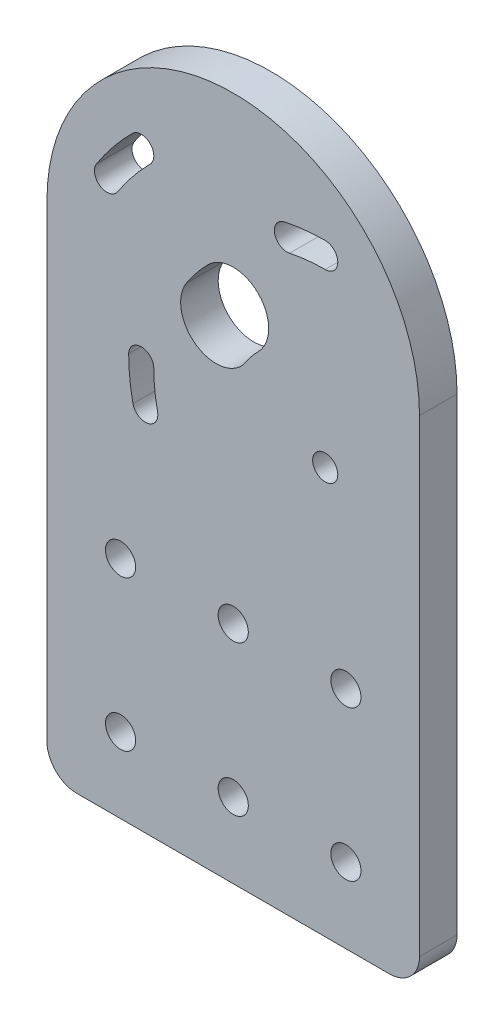
SolidWorks part; units mm, degrees
ref_plane "Front Plane" through (0, 0, 0) normal (0, 0, 1) x (1, 0, 0)
ref_plane "Top Plane" through (0, 0, 0) normal (0, 1, 0) x (1, 0, 0)
ref_plane "Right Plane" through (0, 0, 0) normal (1, 0, 0) x (0, 0, -1)
sketch "Sketch1" plane through (0, 0, 0) normal (0, 0, 1) x (1, 0, 0)
  line L0 (0, 0) -> (-11948.862, 0) construction
  line L1 (-0.5397, 50.8) -> (-11949.4017, 50.8) construction
  line L2 (31.5, 0) -> (31.5, 84.3)
  line L3 (-31.5, 84.3) -> (-31.5, 0)
  line L4 (-31.5, 0) -> (31.5, 0)
  line L5 (19.05, 12.7) -> (0, 12.7) construction
  line L6 (19.05, 12.7) -> (19.05, 38.1) construction
  line L7 (31.5, 12.7) -> (19.05, 12.7) construction
  line L8 (19.05, 12.7) -> (19.05, 0) construction
  line L9 (-31.5, 38.1) -> (-19.05, 38.1) construction
  line L10 (-19.05, 38.1) -> (-19.05, 50.8) construction
  line L11 (9.0877, 99.1765) -> (15.5563, 68.7437) construction
  line L12 (15.5563, 68.7437) -> (15.5563, 99.8563) construction
  line L13 (-15.5563, 68.7437) -> (15.5563, 68.7437) construction
  line L14 (15.5563, 68.7437) -> (-14.8765, 62.275) construction
  line L15 (-21.3452, 92.7078) -> (15.5563, 68.7437) construction
  line L16 (15.5563, 68.7437) -> (-15.5563, 99.8563) construction
  line L17 (-2.8944, 80.7257) -> (15.5563, 68.7437) construction
  line L18 (15.5563, 68.7437) -> (0, 84.3) construction
  circle A0 centre (0, 84.3) radius 33.5 construction
  circle A1 centre (0, 84.3) radius 22 construction
  circle A2 centre (-15.5563, 99.8563) radius 2.125 construction
  circle A3 centre (15.5563, 99.8563) radius 2.125 construction
  circle A4 centre (15.5563, 68.7437) radius 2.125
  circle A5 centre (-15.5563, 68.7437) radius 2.125 construction
  arc A6 (31.5, 84.3) -> (-31.5, 84.3) centre (0, 84.3) ccw
  circle A7 centre (19.05, 12.7) radius 2.5527
  circle A8 centre (0, 12.7) radius 2.5527
  circle A9 centre (0, 38.1) radius 2.5527
  circle A10 centre (19.05, 38.1) radius 2.5527
  circle A11 centre (-19.05, 12.7) radius 2.5527
  circle A12 centre (-19.05, 38.1) radius 2.5527
  circle A13 centre (0, 84.3) radius 6 construction
  arc A17 (9.0877, 99.1765) -> (15.5563, 99.8563) centre (15.5563, 68.7437) cw construction
  arc A18 (15.5563, 101.9813) -> (8.6458, 101.255) centre (15.5563, 68.7437) ccw
  arc A19 (15.5563, 97.7313) -> (9.5295, 97.0979) centre (15.5563, 68.7437) ccw
  arc A20 (15.5563, 97.7313) -> (15.5563, 101.9813) centre (15.5563, 99.8563) ccw
  arc A21 (8.6458, 101.255) -> (9.5295, 97.0979) centre (9.0877, 99.1765) ccw
  arc A22 (-15.5563, 68.7437) -> (-14.8765, 62.275) centre (15.5563, 68.7437) ccw construction
  arc A23 (-17.6813, 68.7437) -> (-16.955, 61.8331) centre (15.5563, 68.7437) ccw
  arc A24 (-13.4313, 68.7437) -> (-12.7979, 62.7168) centre (15.5563, 68.7437) ccw
  arc A25 (-13.4313, 68.7437) -> (-17.6813, 68.7437) centre (-15.5563, 68.7437) ccw
  arc A26 (-16.955, 61.8331) -> (-12.7979, 62.7168) centre (-14.8765, 62.275) ccw
  arc A27 (-15.5563, 99.8563) -> (-21.3452, 92.7078) centre (15.5563, 68.7437) ccw construction
  arc A28 (-17.059, 101.359) -> (-23.1273, 93.8651) centre (15.5563, 68.7437) ccw
  arc A29 (-14.0537, 98.3537) -> (-19.563, 91.5504) centre (15.5563, 68.7437) ccw
  arc A30 (-14.0537, 98.3537) -> (-17.059, 101.359) centre (-15.5563, 99.8563) ccw
  arc A31 (-23.1273, 93.8651) -> (-19.563, 91.5504) centre (-21.3452, 92.7078) ccw
  arc A32 (0, 84.3) -> (-2.8944, 80.7257) centre (15.5563, 68.7437) ccw construction
  arc A33 (-4.2426, 88.5426) -> (-7.9264, 83.9935) centre (15.5563, 68.7437) ccw
  arc A34 (4.2426, 80.0574) -> (2.1376, 77.4579) centre (15.5563, 68.7437) ccw
  arc A35 (4.2426, 80.0574) -> (-4.2426, 88.5426) centre (0, 84.3) ccw
  arc A36 (-7.9264, 83.9935) -> (2.1376, 77.4579) centre (-2.8944, 80.7257) ccw
  point P19 (0, 84.3)
  point P42 (12.3042, 99.6859)
  point P48 (-15.3859, 65.4915)
  point P60 (-18.6381, 96.4337)
  point P69 (-1.5409, 82.5887)
  dimension "D2" = 67
  dimension "D3" = 44
  dimension "D4" = 4.25
  dimension "D6" = 31.5
  dimension "D10" = 5.1054
  dimension "D11" = 25.4
  dimension "D13" = 12
  dimension "D15" = 12
  dimension "D1" = 50.8
  dimension "D9" = 90
  dimension "D12" = 19.05
  dimension "D14" = 12
  dimension "D16" = 12
  dimension "D17" = 12
  dimension "D7" = 3
  dimension "D8" = 2
  dimension "D5" = 4
extrude "Boss-Extrude1" add sketch "Sketch1" along normal blind 6.35
fillet "Fillet1" radius 5.08 2 edges at (-31.5, 0, 3.175) (31.5, 0, 3.175)
